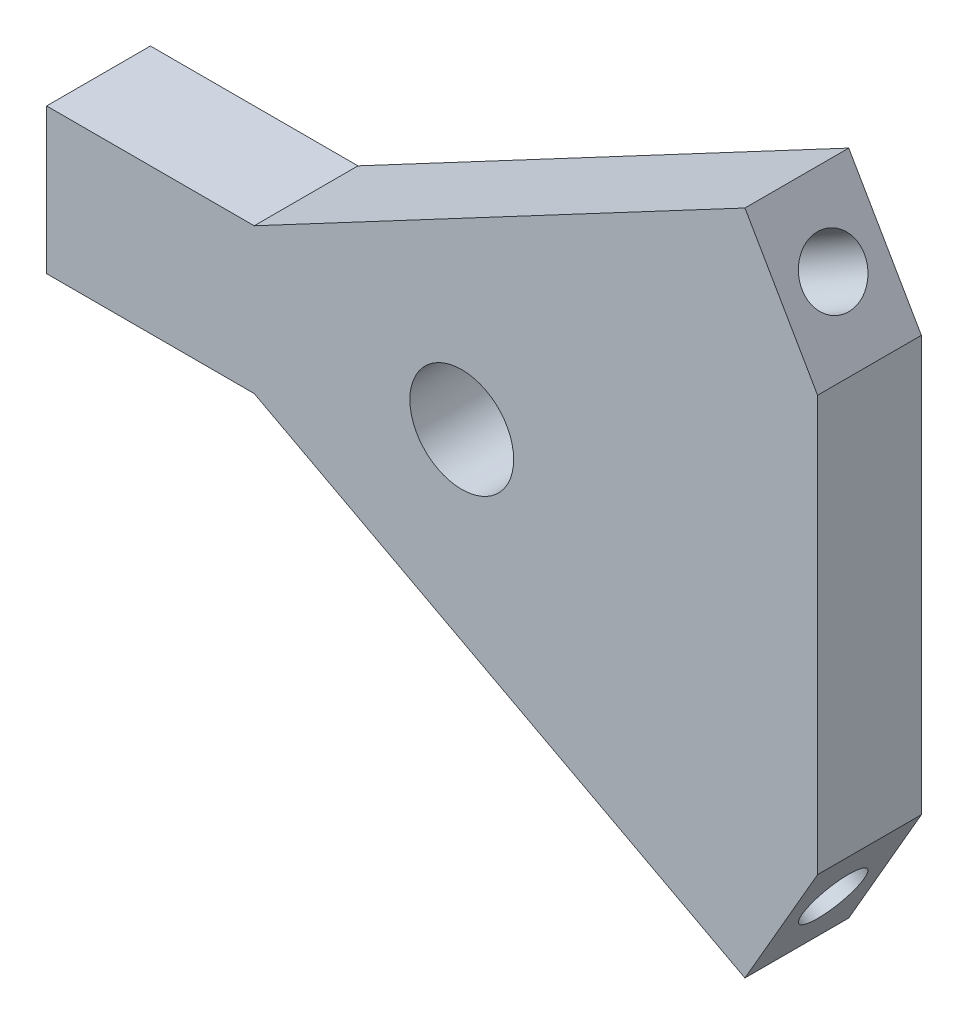
SolidWorks part; units mm, degrees
ref_plane "Plan de face" through (0, 0, 0) normal (0, 0, 1) x (1, 0, 0)
ref_plane "Plan de dessus" through (0, 0, 0) normal (0, 1, 0) x (1, 0, 0)
ref_plane "Plan de droite" through (0, 0, 0) normal (1, 0, 0) x (0, 0, -1)
sketch "Esquisse1" plane through (0, 0, 0) normal (0, 0, 1) x (1, 0, 0)
  line L0 (-20, -7) -> (-20, 7)
  line L1 (-20, 7) -> (0, 7)
  line L2 (0, 7) -> (47.282, 32.1244)
  line L3 (54.282, 20) -> (54.282, -20)
  line L4 (47.282, 32.1244) -> (54.282, 20)
  line L5 (-64.04, 0) -> (20.5013, 0) construction
  line L6 (47.282, -32.1244) -> (54.282, -20)
  line L7 (47.282, 32.1244) -> (23.6391, 18.4741) construction
  line L8 (23.6391, 18.4741) -> (30.6391, 6.3497) construction
  line L9 (0, -7) -> (47.282, -32.1244)
  line L10 (-20, -7) -> (0, -7)
  line L11 (30.6391, 6.3497) -> (54.282, 20) construction
  line L12 (47.282, -32.1244) -> (32.2056, -23.42) construction
  line L13 (32.2056, -23.42) -> (39.2056, -11.2956) construction
  line L14 (39.2056, -11.2956) -> (54.282, -20) construction
  dimension "D1" = 14
  dimension "D2" = 14
  dimension "D3" = 20
  dimension "D4" = 150
  dimension "D5" = 0
  dimension "D6" = 60
  dimension "D7" = 14
  dimension "D8" = 40
extrude "Boss.-Extru.2" add sketch "Esquisse1" along normal blind 10
sketch "Esquisse4" plane through (-20, 0, 0) normal (-1, 0, 0) x (0, 0, 1)
  line L0 (0, 0) -> (10, 0) construction
  line L1 (0, 7) -> (0, -7) construction
  line L2 (10, 7) -> (10, -7) construction
  circle A0 centre (5, 0) radius 3
  point P8 (0, 0)
  dimension "D1" = 6
extrude "Enlèv. mat.-Extru.3" cut sketch "Esquisse4" against normal blind 20
sketch "Esquisse6" plane through (49.3718, 28.5048, 0) normal (0.866, 0.5, 0) x (0.5, -0.866, 0)
  line L0 (2.8205, 0) -> (2.8205, -10) construction
  line L1 (9.8205, 0) -> (-4.1795, 0) construction
  line L2 (9.8205, -10) -> (-4.1795, -10) construction
  circle A0 centre (2.8205, -5) radius 3
  point P8 (2.8205, -5)
  dimension "D1" = 6
extrude "Enlèv. mat.-Extru.4" cut sketch "Esquisse6" against normal blind 20
sketch "Esquisse7" plane through (49.3718, -28.5048, 0) normal (0.866, -0.5, 0) x (-0.5, -0.866, 0)
  line L0 (-9.8205, -5) -> (4.1795, -5) construction
  line L1 (-9.8205, -10) -> (-9.8205, 0) construction
  line L2 (4.1795, -10) -> (4.1795, 0) construction
  circle A0 centre (-2.8205, -5) radius 3
  point P8 (0, 0)
  dimension "D1" = 6
extrude "Enlèv. mat.-Extru.5" cut sketch "Esquisse7" against normal blind 20
sketch "Esquisse8" plane through (0, 0, 0) normal (0, 0, -1) x (-1, 0, 0)
  line L0 (20, 7) -> (20, -7) construction
  circle A0 centre (-20, 0) radius 5
  point P4 (20, 0)
  dimension "D2" = 10
  dimension "D1" = 40
extrude "Enlèv. mat.-Extru.6" cut sketch "Esquisse8" against normal blind 20
